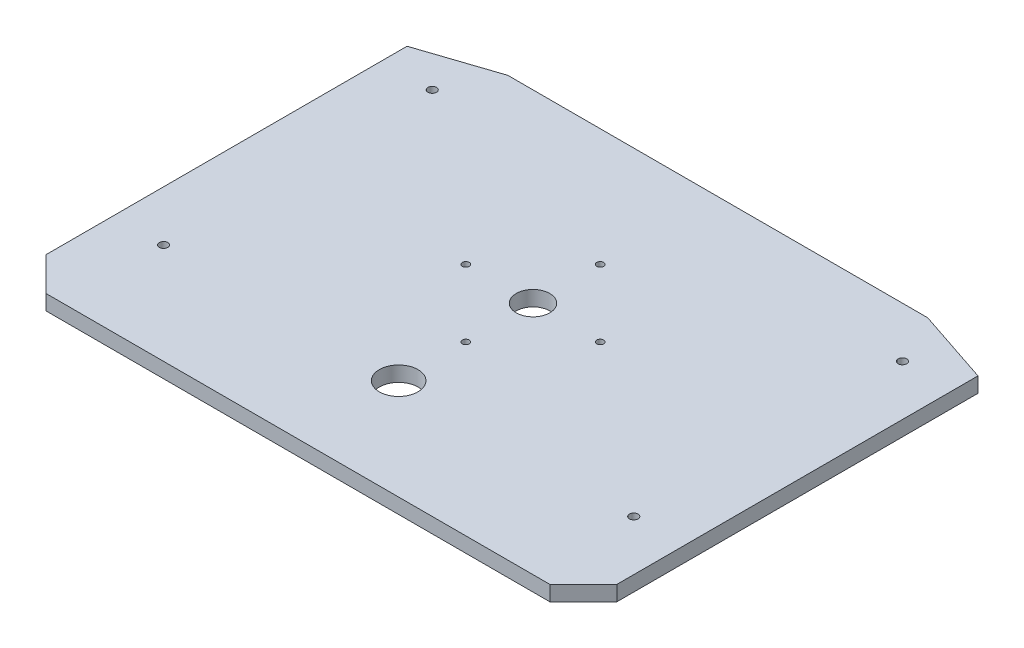
SolidWorks part; units mm, degrees
ref_plane "Plan de face" through (0, 0, 0) normal (0, 0, 1) x (1, 0, 0)
ref_plane "Plan de dessus" through (0, 0, 0) normal (0, 1, 0) x (1, 0, 0)
ref_plane "Plan de droite" through (0, 0, 0) normal (1, 0, 0) x (0, 0, -1)
sketch "Esquisse3" plane through (0, 0, 0) normal (0, 1, 0) x (1, 0, 0)
  line L0 (-281.7629, 0) -> (308.2067, 0) construction
  line L1 (0, 166.4902) -> (0, -269.1166) construction
  line L4 (-160, -46) -> (-160, 46) construction
  line L5 (-156, 50) -> (-149, 50) construction
  line L6 (-145, 46) -> (-145, -46) construction
  line L7 (-105, 0) -> (-105, 31) construction
  line L8 (-101, 35) -> (-74, 35) construction
  line L9 (-70, 31) -> (-70, -31) construction
  line L11 (-105, 0) -> (-105, -31) construction
  line L12 (-101, -35) -> (-74, -35) construction
  line L13 (-156, -50) -> (-149, -50) construction
  line L17 (156, 50) -> (149, 50) construction
  line L18 (156, -50) -> (149, -50) construction
  line L19 (145, 46) -> (145, -46) construction
  line L20 (160, -46) -> (160, 46) construction
  line L21 (105, 0) -> (105, 31) construction
  line L22 (101, -35) -> (74, -35) construction
  line L23 (105, 0) -> (105, -31) construction
  line L24 (70, 31) -> (70, -31) construction
  line L25 (101, 35) -> (74, 35) construction
  line L26 (125, 110) -> (-125, 110)
  line L34 (-170, 95) -> (-125, 110)
  line L35 (170, 95) -> (125, 110)
  line L38 (-170, 95) -> (-170, 0)
  line L39 (-170, 0) -> (-170, -120)
  line L40 (170, -120) -> (170, 0)
  line L41 (170, 0) -> (170, 95)
  line L43 (-170, -120) -> (-150, -140)
  line L44 (150, -140) -> (170, -120)
  line L45 (-150, -140) -> (-120, -140)
  line L46 (-120, -140) -> (-120, -55) construction
  line L47 (-120, -55) -> (120, -55) construction
  line L48 (120, -55) -> (120, -140) construction
  line L49 (120, -140) -> (150, -140)
  line L50 (-170, 95) -> (170, 95) construction
  line L51 (-170, 0) -> (-220, 0) construction
  line L52 (-220, 0) -> (-170, 95) construction
  line L53 (-220, 0) -> (-170, -120) construction
  line L54 (-130, -140) -> (-130, -220) construction
  line L55 (-130, -220) -> (130, -220) construction
  line L56 (130, -140) -> (130, -220) construction
  line L57 (-170, -120) -> (-130, -220) construction
  line L58 (-120, -140) -> (120, -140)
  arc A0 (-149, 50) -> (-145, 46) centre (-149, 46) cw construction
  arc A1 (-74, 35) -> (-70, 31) centre (-74, 31) cw construction
  arc A2 (-105, 31) -> (-101, 35) centre (-101, 31) cw construction
  arc A3 (-160, 46) -> (-156, 50) centre (-156, 46) cw construction
  arc A4 (-105, -31) -> (-101, -35) centre (-101, -31) ccw construction
  arc A5 (-74, -35) -> (-70, -31) centre (-74, -31) ccw construction
  arc A6 (-160, -46) -> (-156, -50) centre (-156, -46) ccw construction
  arc A7 (-149, -50) -> (-145, -46) centre (-149, -46) ccw construction
  arc A8 (149, 50) -> (145, 46) centre (149, 46) ccw construction
  arc A9 (160, 46) -> (156, 50) centre (156, 46) ccw construction
  arc A10 (149, -50) -> (145, -46) centre (149, -46) cw construction
  arc A11 (160, -46) -> (156, -50) centre (156, -46) cw construction
  arc A12 (74, -35) -> (70, -31) centre (74, -31) cw construction
  arc A13 (105, -31) -> (101, -35) centre (101, -31) cw construction
  arc A14 (105, 31) -> (101, 35) centre (101, 31) ccw construction
  arc A15 (74, 35) -> (70, 31) centre (74, 31) ccw construction
  circle A16 centre (-140, 80) radius 2.55
  circle A17 centre (-140, -80) radius 2.55
  circle A18 centre (140, -80) radius 2.55
  circle A19 centre (140, 80) radius 2.55
  point P1 (0, 0)
  point P6 (-170, 110)
  point P16 (-105, 15.5)
  point P19 (-145, 50)
  point P22 (-70, 35)
  point P25 (-105, 35)
  point P28 (-160, 50)
  point P32 (-70, 0)
  point P37 (-105, -35)
  point P38 (-70, -35)
  point P40 (-145, 0)
  point P41 (-160, 0)
  point P45 (-160, -50)
  point P46 (-145, -50)
  point P47 (0, 110)
  point P48 (-170, 0)
  point P51 (0, -110)
  point P64 (145, -50)
  point P65 (160, -50)
  point P75 (70, -35)
  point P76 (105, -35)
  point P81 (105, 35)
  point P82 (70, 35)
  point P83 (0, -269.1166)
  point P85 (0, 110)
  point P94 (-170, 0)
  point P97 (170, 0)
  point P100 (0, -130)
  point P104 (0, 0)
  dimension "D7" = 4
  dimension "D10" = 5.1
  dimension "D2" = 250
  dimension "D3" = 35
  dimension "D4" = 15
  dimension "D5" = 70
  dimension "D6" = 40
  dimension "D14" = 30
  dimension "D13" = 110
  dimension "D8" = 35
  dimension "D9" = 50
  dimension "D11" = 240
  dimension "D12" = 340
  dimension "D15" = 120
  dimension "D16" = 95
  dimension "D17" = 140
  dimension "D18" = 80
  dimension "D19" = 85
  dimension "D20" = 140
  dimension "D21" = 125
  dimension "D22" = 28.2843
  dimension "D23" = 47.4342
  dimension "D24" = 120
  dimension "D25" = 50
  dimension "D26" = 130
  dimension "D27" = 107.3546
  dimension "D28" = 80
  dimension "D29" = 10
  dimension "D30" = 107.7033
  dimension "D31" = 130
extrude "structure" add sketch "Esquisse3" against normal blind 9
sketch "Esquisse4" plane through (0, 0, 0) normal (0, 1, 0) x (1, 0, 0)
  line L0 (0, 110) -> (0, -140) construction
  line L1 (125, 110) -> (-125, 110) construction
  line L2 (-150, -140) -> (150, -140) construction
  line L3 (-170, 0) -> (170, 0) construction
  line L4 (-170, 95) -> (-170, -120) construction
  line L5 (170, -120) -> (170, 95) construction
  circle A0 centre (0, 0) radius 10
  circle A1 centre (0, -80) radius 11.5
  circle A2 centre (0, 0) radius 40 construction
  circle A3 centre (0, 40) radius 2.05
  circle A4 centre (40, 0) radius 2.05
  circle A5 centre (0, -40) radius 2.05
  circle A6 centre (-40, 0) radius 2.05
  circle A7 centre (0, 0) radius 30.8 construction
  point P29 (0, 0)
  dimension "D1" = 23
  dimension "D3" = 20
  dimension "D4" = 4.1
  dimension "D6" = 80
  dimension "D7" = 61.6
  dimension "D2" = 80
  dimension "D5" = 4
extrude "Enlèv. mat.-Extru.1" cut sketch "Esquisse4" against normal blind 10
